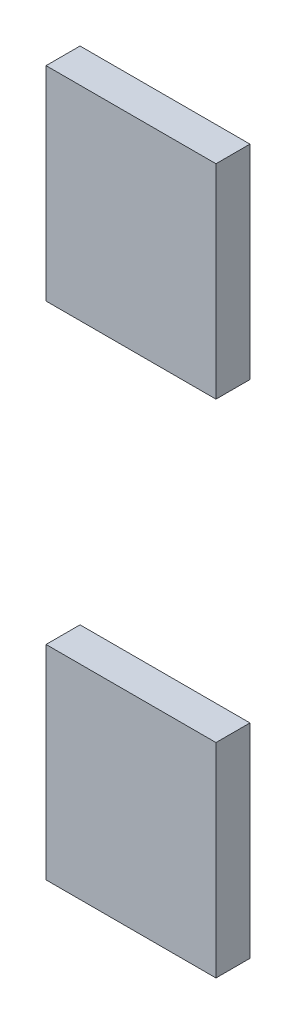
SolidWorks part; units mm, degrees
ref_plane "Front Plane" through (0, 0, 0) normal (0, 0, 1) x (1, 0, 0)
ref_plane "Top Plane" through (0, 0, 0) normal (0, 1, 0) x (1, 0, 0)
ref_plane "Right Plane" through (0, 0, 0) normal (1, 0, 0) x (0, 0, -1)
sketch "BODY" plane through (0, 0, 0) normal (0, 0, 1) x (1, 0, 0)
  line L0 (-7, 14) -> (-7, -14) construction
  line L1 (-9.5, 4.375) -> (-4.5, 4.375)
  line L2 (-9.5, 4.375) -> (-9.5, 10.375)
  line L3 (-9.5, 10.375) -> (-4.5, 10.375)
  line L4 (-4.5, 4.375) -> (-4.5, 10.375)
  line L5 (-12, 0.75) -> (-12, 14) construction
  line L6 (-12, 7.375) -> (-2, 7.375) construction
  line L7 (-12, 0) -> (0, 0) construction
  line L8 (-9.5, -4.375) -> (-4.5, -4.375)
  line L9 (-4.5, -4.375) -> (-4.5, -10.375)
  line L10 (-9.5, -10.375) -> (-4.5, -10.375)
  line L11 (-9.5, -4.375) -> (-9.5, -10.375)
  point P4 (-7, 14)
  point P7 (-7, 4.375)
  point P8 (-9.5, 7.375)
  dimension "D1" = 6
  dimension "D2" = 5
  dimension "D3" = 13.25
extrude "Body Extrude" add sketch "BODY" along normal blind 1
